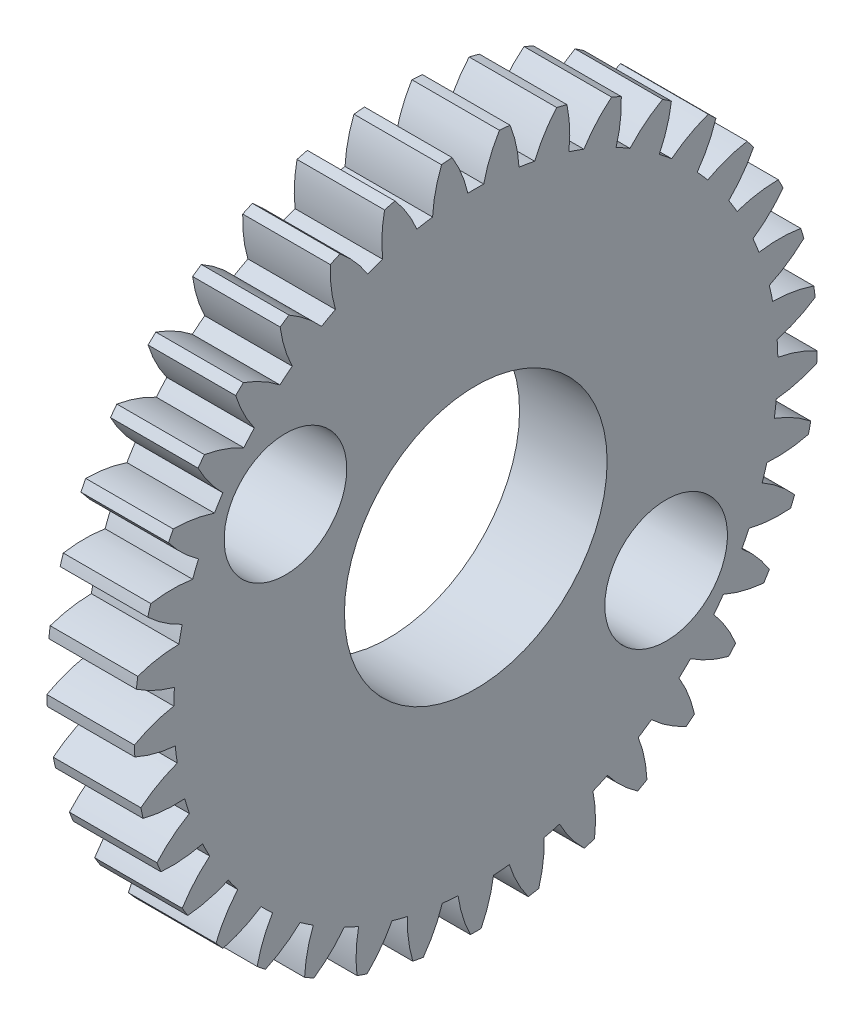
SolidWorks part; units mm, degrees
ref_plane "Plane1" through (0, 0, 0) normal (0, 0, 1) x (1, 0, 0)
ref_plane "Plane2" through (0, 0, 0) normal (0, 1, 0) x (1, 0, 0)
ref_plane "Plane3" through (0, 0, 0) normal (1, 0, 0) x (0, 0, -1)
sketch "HoldingSke" plane through (0, 0, 0) normal (0, 1, 0) x (1, 0, 0)
  line L0 (0, 0) -> (1.3311, -1.003)
  line L1 (-15, 0) -> (100, 0) construction
  line L2 (0, 0) -> (-2.1039, 2.3779)
  line L3 (0, 0) -> (-11.863, 4.5341)
  line L4 (0, 0) -> (6.897, 5.1973)
  line L5 (0, 0) -> (-46.8476, -17.4728)
  line L6 (0, 0) -> (-2.4869, -1.6779)
  line L7 (-2.1039, 2.3779) -> (8.6586, 51.2059)
  line L8 (-76.2, 54.61) -> (-74.8, 54.61)
  line L9 (-71.009, 38.7566) -> (-53.1078, 45.2721)
  line L10 (-76.2, 71.12) -> (104.1128, 71.12)
  line L11 (0, 0) -> (-3, 0)
  line L12 (-76.2, 101.6) -> (-76.177, 101.6)
  line L13 (24.9733, 27.94) -> (52.9518, 28.4284)
  line L14 (24.9733, 27.94) -> (24.9743, 27.94)
  line L15 (24.9733, 27.94) -> (100.4006, 29.5858)
  line L16 (-63.627, -0.6) -> (-12.827, -0.6)
  circle A0 centre (0, 0) radius 4.5
  circle A1 centre (0, 0) radius 10.349
  circle A2 centre (0, 0) radius 37.5
  circle A3 centre (0, 0) radius 4.5
  dimension "MHD" = 20.698
  dimension "Hub_dia" = 75
  dimension "Bore" = 9
  dimension "MBD" = 9
  dimension "Num_teeth" = 37
  dimension "Pitch" = 1.6667
  dimension "Overall_len" = 50
  dimension "Show_teeth" = 37
  dimension "Thickness" = 3
  dimension "OAL" = 50.0001
  dimension "T_dim" = 1.4
  dimension "Ap" = 20
  dimension "H" = 19.05
  dimension "Pitch_radius" = 180.3128
  dimension "Width" = 3
  dimension "Backlash" = 0.023
  dimension "Addendum_fac" = 1
  dimension "Dedendum_fac" = 1.25
  dimension "Clearance_fac" = 0.25
  dimension "Dedendum_add" = 0.001
  dimension "Module" = 0.6
sketch "BasProSke" plane through (0, 0, 0) normal (0, 1, 0) x (1, 0, 0)
  line L0 (-10, 0) -> (60, 0) construction
  line L1 (0, 0) -> (0, 11.7)
  line L2 (0, 0) -> (3, 0)
  line L3 (3, 0) -> (3, 11.7)
  line L4 (3, 11.7) -> (0, 11.7)
  dimension "Thickness" = 3
  dimension "Diameter" = 23.4
revolve "Base-Revolve" add sketch "BasProSke" angle 360 about L0
sketch "TooCutSke" plane through (0, 0, 0) normal (1, 0, 0) x (0, 0, -1)
  line L1 (0, 0) -> (0, 107) construction
  line L2 (0, 0) -> (-0.5113, 11.0882) construction
  line L3 (0, 0) -> (-1.8813, 22.1034) construction
  line L4 (-0.5113, 11.0882) -> (-0.9406, 11.0517) construction
  arc A0 (0.2721, 10.3454) -> (-0.2721, 10.3454) centre (0, 0) ccw
  arc A1 (0.8254, 11.6963) -> (-0.8254, 11.6963) centre (0, 0) ccw
  circle A2 centre (0, 0) radius 11.1 construction
  circle A3 centre (0, 0) radius 10.4306 construction
  arc A4 (-0.2721, 10.3454) -> (-0.8254, 11.6963) centre (-4.6015, 9.3607) ccw
  arc A5 (0.8254, 11.6963) -> (0.2721, 10.3454) centre (4.6015, 9.3607) ccw
  dimension "Root_dia" = 20.698
  dimension "Overcut_dia" = 23.4508
  dimension "Pitch_dia" = 22.2
  dimension "Base_dia" = 20.8612
  dimension "Flank_rad" = 4.44
  dimension "Half_ang" = 4.865
  dimension "Half_CT" = 0.4308
extrude "ToothCut" cut sketch "TooCutSke" along normal through all
fillet "Breaks" [suppressed] radius 0.012
fillet "RootFillets" [suppressed] radius 0.151
pattern_circular "TeethCuts" count 37 every 9.73 about axis through (-10, 0, 0) along (1, 0, 0) of "ToothCut", "RootFillets", "Breaks"
sketch "HubNeaOneSke" plane through (0, 0, 0) normal (-1, 0, 0) x (0, 0, 1)
  circle A0 centre (0, 0) radius 10.349
  dimension "Diameter" = 20.698
extrude "HubNearOne" [suppressed] add sketch "HubNeaOneSke" along normal blind 47.0001
sketch "HubNeaBotSke" plane through (0, 0, 0) normal (-1, 0, 0) x (0, 0, 1)
  circle A0 centre (0, 0) radius 10.349
  dimension "Diameter" = 20.698
extrude "HubNearBoth" [suppressed] add sketch "HubNeaBotSke" along normal blind 23.5
ref_plane "FarPln" through (3, 0, 0) normal (1, 0, 0) x (0, 0, -1)
sketch "HubFarSke" plane through (3, 0, 0) normal (1, 0, 0) x (0, 0, -1)
  circle A0 centre (0, 0) radius 10.349
  dimension "Diameter" = 20.698
extrude "HubFar" [suppressed] add sketch "HubFarSke" along normal blind 23.5
sketch "BorSke" plane through (0, 0, 0) normal (1, 0, 0) x (0, 0, -1)
  circle A0 centre (0, 0) radius 4.5
  dimension "Diameter" = 9
extrude "Bore" cut sketch "BorSke" along normal mid plane 100.0001
sketch "KeySke" plane through (0, 0, 0) normal (1, 0, 0) x (0, 0, -1)
  line L0 (-1.5, 0) -> (-1.5, 5.9)
  line L1 (-1.5, 5.9) -> (1.5, 5.9)
  line L2 (1.5, 5.9) -> (1.5, 0)
  line L3 (0, 0) -> (0, 34) construction
  line L4 (-1.5, 0) -> (1.5, 0)
  dimension "Width" = 3
  dimension "Offset" = 5.9
extrude "Keyway" [suppressed] cut sketch "KeySke" along normal mid plane 100.0001
pattern_circular "Keyway2" [suppressed] count 2 every 90 about axis through (-10, 0, 0) along (1, 0, 0)
sketch "Esquisse1" plane through (3, 0, 0) normal (1, 0, 0) x (0, 0, -1)
  circle A0 centre (-6.5212, 4.243) radius 2.1
  dimension "D1" = 4.2
  dimension "D2" = 7.78
extrude "Enlèv. mat.-Extru.1" cut sketch "Esquisse1" against normal through all
pattern_circular "Répétition circulaire1" count 2 over 360 about axis through (0, 0, 0) along (1, 0, 0) of "Enlèv. mat.-Extru.1"
equation "' \"Module@HoldingSke\" = 6.35"
equation "' \"Num_teeth@HoldingSke\" = 12"
equation "' \"Ap@HoldingSke\" =  20"
equation "' \"Ap@HoldingSke\" = 20"
equation "' \"Width@HoldingSke\" = 0.5 * 25.4"
equation "' \"Hub_dia@HoldingSke\"= 1 * 25.4"
equation "' \"Hub_dia@HoldingSke\" = 1 * 25.4"
equation "' \"Overall_len@HoldingSke\" = 1.0 * 25.4"
equation "' \"Bore@HoldingSke\" = 0.75 * 25.4"
equation "' \"T_dim@HoldingSke\" = 0.1 * 25.4"
equation "' \"Width@KeySke\" = 0.25 * 25.4"
equation "' \"Show_teeth@HoldingSke\" = 13"
equation "' \"Backlash@HoldingSke\" = 0.009 * 25.4"
equation "' \"Addendum_fac@HoldingSke\" = 1.0"
equation "' \"Dedendum_fac@HoldingSke\" = 1.25"
equation "' \"Dedendum_add@HoldingSke\" = 0.00005 * 25.4"
equation "' \"Clearance_fac@HoldingSke\" = 0.25"
equation "\"Pitch@HoldingSke\" = 1 / \"Module@HoldingSke\""
equation "\"Overcut_dia@TooCutSke\" = (\"Num_teeth@HoldingSke\" + 2 * \"Addendum_fac@HoldingSke\") / \"Pitch@HoldingSke\" + 0.002 * 25.4"
equation "\"Pitch_dia@TooCutSke\" = \"Num_teeth@HoldingSke\" / \"Pitch@HoldingSke\""
equation "\"Base_dia@TooCutSke\" = \"Num_teeth@HoldingSke\" / \"Pitch@HoldingSke\" * cos((\"Ap@HoldingSke\"  * 3.14159265 / 180))"
equation "\"Root_dia@TooCutSke\" = (\"Num_teeth@HoldingSke\" + 2) / \"Pitch@HoldingSke\" - 2 * (\"Addendum_fac@HoldingSke\" + \"Dedendum_fac@HoldingSke\") / \"Pitch@HoldingSke\" - \"Dedendum_add@HoldingSke\" * 2"
equation "\"Half_ang@TooCutSke\" = 180 / \"Num_teeth@HoldingSke\""
equation "\"Half_CT@TooCutSke\" = \"Num_teeth@HoldingSke\" / \"Pitch@HoldingSke\" * sin((3.14159265 / 2 / \"Num_teeth@HoldingSke\")) / 2 - 7 * \"Backlash@HoldingSke\" / 4"
equation "\"Flank_rad@TooCutSke\" = \"Num_teeth@HoldingSke\" / \"Pitch@HoldingSke\" / 5"
equation "\"Radius@RootFillets\" = \"Clearance_fac@HoldingSke\" / \"Pitch@HoldingSke\" + \"Dedendum_add@HoldingSke\""
equation "\"Break_rad@Breaks\" = 0.02 / \"Pitch@HoldingSke\""
equation "\"Thickness@HoldingSke\" = \"Width@HoldingSke\""
equation "\"OAL@HoldingSke\" = \"Thickness@HoldingSke\""
equation "\"MHD@HoldingSke\" = (\"Num_teeth@HoldingSke\" + 2) / \"Pitch@HoldingSke\" - 2 * (\"Addendum_fac@HoldingSke\" + \"Dedendum_fac@HoldingSke\")  / \"Pitch@HoldingSke\" - \"Dedendum_add@HoldingSke\" * 2"
equation "\"MBD@HoldingSke\" = (\"Num_teeth@HoldingSke\" + 2) / \"Pitch@HoldingSke\" - 2 * (\"Addendum_fac@HoldingSke\" + \"Dedendum_fac@HoldingSke\")  / \"Pitch@HoldingSke\" - \"Dedendum_add@HoldingSke\" * 2 - 0.002 * 25.4"
equation "\"MHD@HoldingSke\" = ((sgn( \"MHD@HoldingSke\" - \"Hub_dia@HoldingSke\" )-1)*( \"MHD@HoldingSke\" - \"Hub_dia@HoldingSke\" ))/-2+ \"Hub_dia@HoldingSke\""
equation "\"MBD@HoldingSke\" = ((sgn( \"MBD@HoldingSke\" - \"Bore@HoldingSke\" )-1)*( \"MBD@HoldingSke\" - \"Bore@HoldingSke\" ))/-2+ \"Bore@HoldingSke\""
equation "\"OAL@HoldingSke\" = ((sgn( \"OAL@HoldingSke\" - \"Overall_len@HoldingSke\" )+1)*( \"OAL@HoldingSke\" - \"Overall_len@HoldingSke\" ))/2 + \"Overall_len@HoldingSke\" + 0.000002 * 25.4"
equation "\"Num_teeth@TeethCuts\" = int( \"Show_teeth@HoldingSke\" ) + 1"
equation "\"Num_teeth@TeethCuts\" = ((sgn( \"Num_teeth@TeethCuts\" - \"Num_teeth@HoldingSke\" )-1)*( \"Num_teeth@TeethCuts\" - \"Num_teeth@HoldingSke\" ))/-2+ \"Num_teeth@HoldingSke\""
equation "\"Num_teeth@TeethCuts\" = ((sgn( \"Num_teeth@TeethCuts\" - 2.0)+1)*( \"Num_teeth@TeethCuts\" - 2.0))/2 +2.0"
equation "\"Angle@TeethCuts\" = 360.0 / \"Num_teeth@HoldingSke\""
equation "\"Diameter@BasProSke\" = (\"Num_teeth@HoldingSke\" + 2 * \"Addendum_fac@HoldingSke\") / \"Pitch@HoldingSke\""
equation "\"Thickness@BasProSke\"  = \"Thickness@HoldingSke\""
equation "' \"Fillet_rad@BasProSke\" =  \"Thickness@HoldingSke\" * 0.05"
equation "' \"Fillet_rad@BasProSke\" = \"Thickness@HoldingSke\" * 0.05"
equation "\"MHD@HoldingSke\" = ((sgn( \"MHD@HoldingSke\" - \"Root_dia@TooCutSke\" )-1)*( \"MHD@HoldingSke\" - \"Root_dia@TooCutSke\" ))/-2+ \"Root_dia@TooCutSke\""
equation "\"Diameter@HubNeaOneSke\" = \"MHD@HoldingSke\""
equation "\"Length@HubNearOne\" = \"OAL@HoldingSke\" - \"Thickness@BasProSke\""
equation "\"Diameter@HubNeaBotSke\" = \"MHD@HoldingSke\""
equation "\"Length@HubNearBoth\" = ( \"OAL@HoldingSke\" - \"Thickness@BasProSke\" ) / 2.0"
equation "\"Thickness@FarPln\" = \"Thickness@BasProSke\""
equation "\"Diameter@HubFarSke\" = \"MHD@HoldingSke\""
equation "\"Length@HubFar\" = ( \"OAL@HoldingSke\" - \"Thickness@BasProSke\" ) / 2.0"
equation "\"Diameter@BorSke\" = \"MBD@HoldingSke\""
equation "\"D1@Bore\" = \"OAL@HoldingSke\" * 2.0"
equation "\"D1@Keyway\" = \"OAL@HoldingSke\" * 2.0"
equation "\"Offset@KeySke\" = \"T_dim@HoldingSke\" + \"MBD@HoldingSke\" / 2.0"
